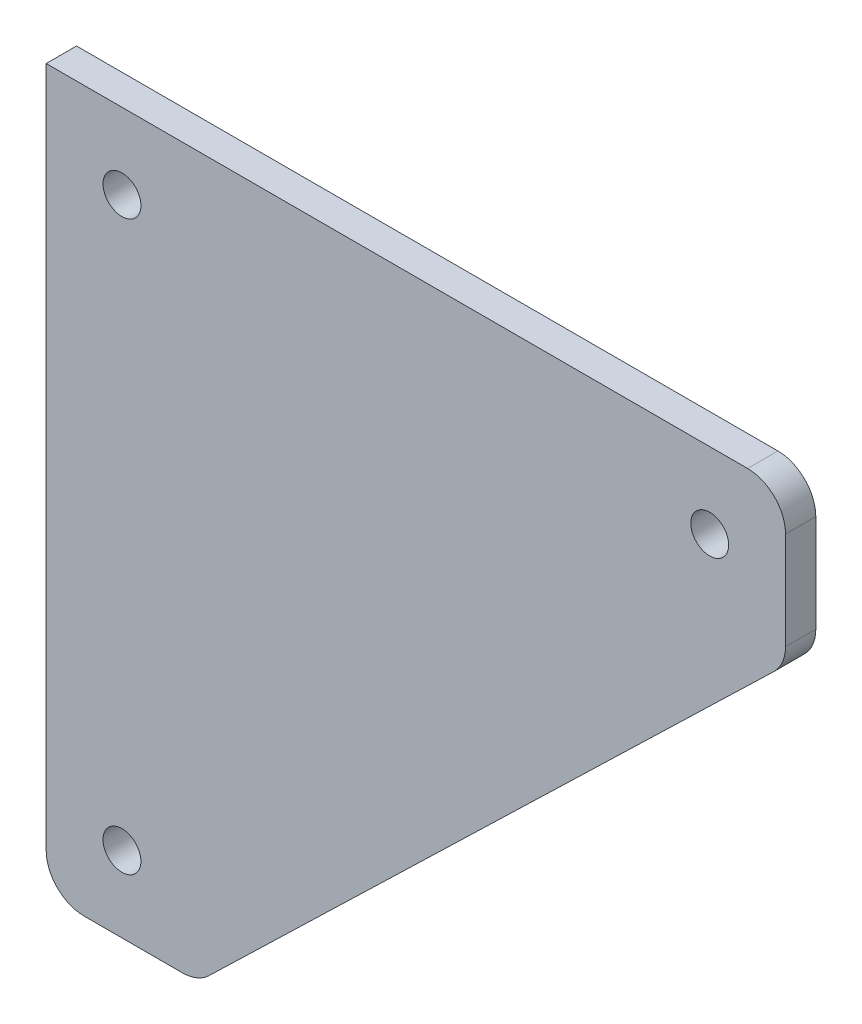
SolidWorks part; units mm, degrees
ref_plane "Plan de face" through (0, 0, 0) normal (0, 0, 1) x (1, 0, 0)
ref_plane "Plan de dessus" through (0, 0, 0) normal (0, 1, 0) x (1, 0, 0)
ref_plane "Plan de droite" through (0, 0, 0) normal (1, 0, 0) x (0, 0, -1)
sketch "Esquisse1" plane through (0, 0, 0) normal (0, 0, 1) x (1, 0, 0)
  line L0 (-46.4576, 41.1511) -> (51.1182, 41.1511)
  line L1 (51.1182, 41.1511) -> (51.1182, 21.1511)
  line L2 (51.1182, 21.1511) -> (-26.4576, -53.7984)
  line L3 (-26.4576, -53.7984) -> (-46.4576, -53.7984)
  line L4 (-46.4576, -53.7984) -> (-46.4576, 41.1511)
  dimension "D1" = 20
  dimension "D2" = 20
extrude "Boss.-Extru.1" add sketch "Esquisse1" along normal blind 4
sketch "Esquisse2" plane through (0, 0, 4) normal (0, 0, 1) x (1, 0, 0)
  line L0 (51.1182, 31.1511) -> (-46.4576, 31.1511) construction
  line L1 (51.1182, 21.1511) -> (51.1182, 41.1511) construction
  line L2 (-46.4576, 41.1511) -> (-46.4576, -53.7984) construction
  line L3 (-36.4576, -53.7984) -> (-36.4576, 41.1511) construction
  line L4 (-46.4576, -53.7984) -> (-26.4576, -53.7984) construction
  line L5 (51.1182, 41.1511) -> (-46.4576, 41.1511) construction
  circle A0 centre (-36.4576, 31.1511) radius 2.5
  circle A1 centre (41.1182, 31.1511) radius 2.5
  circle A2 centre (-36.4576, -43.7984) radius 2.5
  dimension "D1" = 5
  dimension "D2" = 10
  dimension "D3" = 10
extrude "Enlèv. mat.-Extru.1" cut sketch "Esquisse2" against normal up to vertex (4 mm away)
fillet "Congé1" radius 5 4 edges at (51.1182, 41.1511, 2) (51.1182, 21.1511, 2) (-26.4576, -53.7984, 2) (-46.4576, -53.7984, 2)
